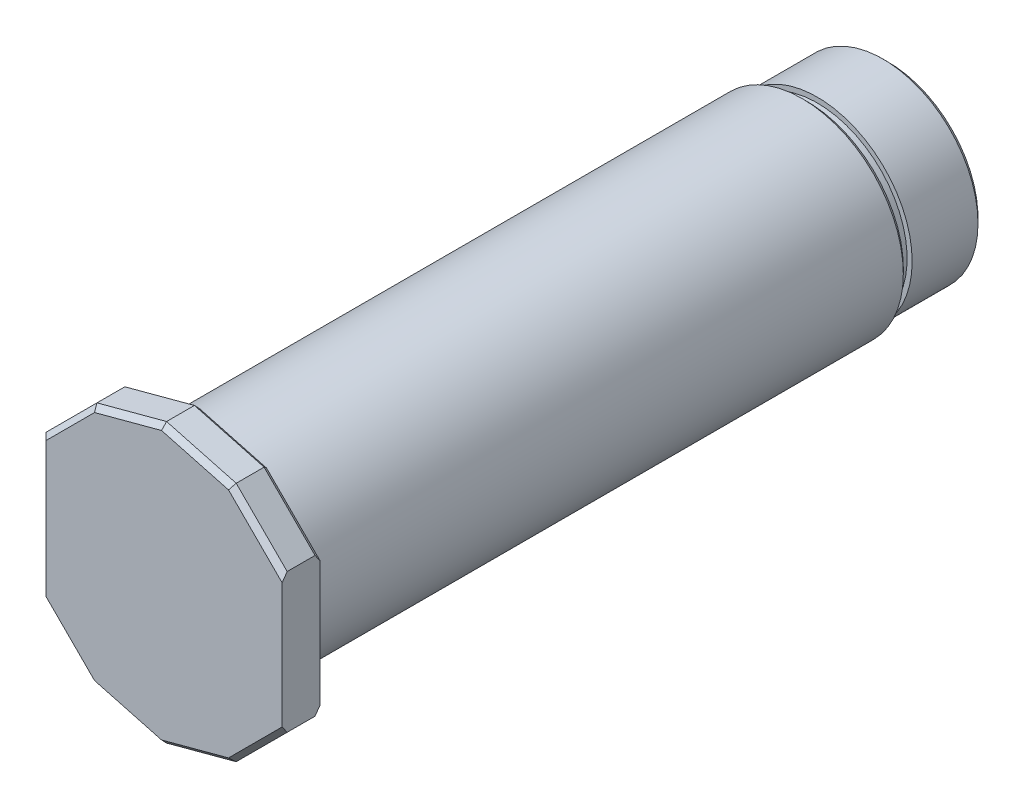
SolidWorks part; units mm, degrees
ref_plane "前视基准面" through (0, 0, 0) normal (0, 0, 1) x (1, 0, 0)
ref_plane "上视基准面" through (0, 0, 0) normal (0, 1, 0) x (1, 0, 0)
ref_plane "右视基准面" through (0, 0, 0) normal (1, 0, 0) x (0, 0, -1)
sketch "草图1" plane through (0, 0, 0) normal (0, 0, 1) x (1, 0, 0)
  line L1 (-27.5, 47.6314) -> (-47.6314, 27.5)
  line L2 (-47.6314, 27.5) -> (-55, 0)
  line L3 (-55, 0) -> (-47.6314, -27.5)
  line L4 (-47.6314, -27.5) -> (-27.5, -47.6314)
  line L5 (-27.5, -47.6314) -> (0, -55)
  line L6 (0, -55) -> (27.5, -47.6314)
  line L7 (27.5, -47.6314) -> (47.6314, -27.5)
  line L8 (47.6314, -27.5) -> (55, 0)
  line L9 (55, 0) -> (47.6314, 27.5)
  line L10 (47.6314, 27.5) -> (27.5, 47.6314)
  line L11 (27.5, 47.6314) -> (0, 55)
  line L12 (0, 55) -> (-27.5, 47.6314)
  circle A0 centre (0, 0) radius 53.1259 construction
  dimension "D1" = 55
extrude "凸台-拉伸1" add sketch "草图1" along normal blind 15
sketch "草图2" plane through (0, 0, 15) normal (0, 0, 1) x (1, 0, 0)
  line L0 (-47.6314, 27.5) -> (-47.6314, -27.5)
  line L1 (-47.6314, -27.5) -> (-55, 0)
  line L2 (-55, 0) -> (-47.6314, 27.5)
  line L3 (47.6314, 27.5) -> (47.6314, -27.5)
  line L4 (47.6314, -27.5) -> (55, 0)
  line L5 (55, 0) -> (47.6314, 27.5)
extrude "切除-拉伸1" cut sketch "草图2" against normal through all
sketch "草图3" plane through (0, 0, 0) normal (0, 0, -1) x (-1, 0, 0)
  circle A0 centre (0, 0) radius 40
  dimension "D1" = 80
extrude "凸台-拉伸2" add sketch "草图3" along normal blind 240
sketch "草图4" plane through (0, 0, -240) normal (0, 0, -1) x (-1, 0, 0)
  circle A0 centre (0, 0) radius 35.5
  dimension "D1" = 71
extrude "凸台-拉伸3" add sketch "草图4" along normal blind 4
sketch "草图5" plane through (0, 0, -244) normal (0, 0, -1) x (-1, 0, 0)
  circle A0 centre (0, 0) radius 37.5
  dimension "D1" = 75
extrude "凸台-拉伸4" add sketch "草图5" along normal blind 28
chamfer "倒角1" distance 2 angle 45 20 edges at (-40, 0, -240) (-37.5, 0, -272) (13.75, -51.3157, 15) (37.5657, -37.5657, 15) (13.75, -51.3157, 0) (37.5657, -37.5657, 0) (13.75, 51.3157, 15) (37.5657, 37.5657, 15) (13.75, 51.3157, 0) (37.5657, 37.5657, 0) (-47.6314, 0, 15) (-37.5657, 37.5657, 15) (-13.75, 51.3157, 15) (-47.6314, 0, 0) (-37.5657, 37.5657, 0) (-13.75, 51.3157, 0) (-13.75, -51.3157, 15) (-37.5657, -37.5657, 15) (-13.75, -51.3157, 0) (-37.5657, -37.5657, 0)
